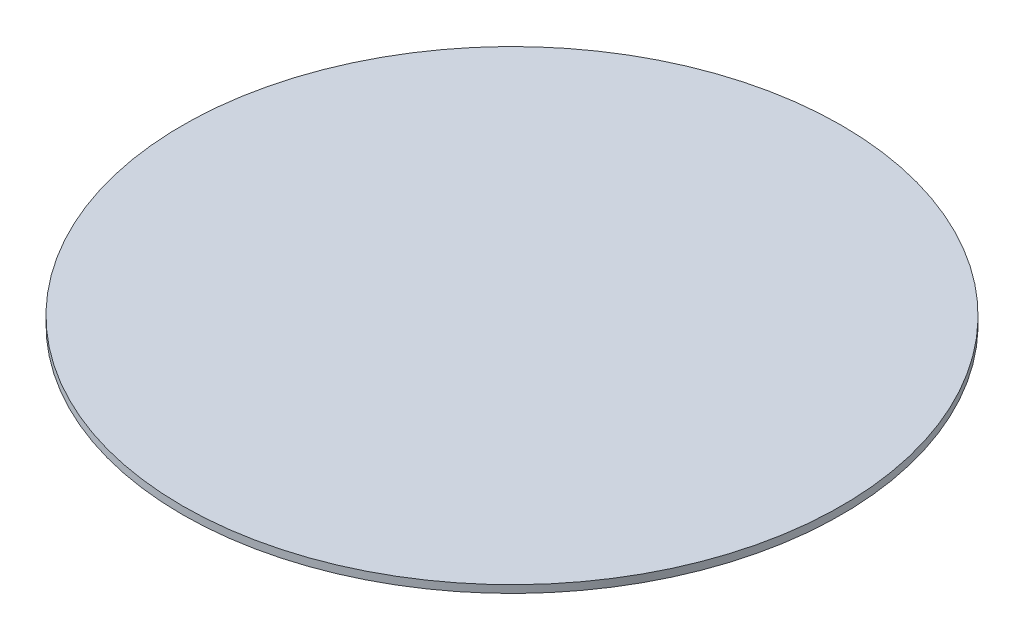
SolidWorks part; units mm, degrees
material "Стекло"
ref_plane "Front" through (0, 0, 0) normal (0, 0, 1) x (1, 0, 0)
ref_plane "Top" through (0, 0, 0) normal (0, 1, 0) x (1, 0, 0)
ref_plane "Right" through (0, 0, 0) normal (1, 0, 0) x (0, 0, -1)
sketch "Эскиз1" plane through (0, 0, 0) normal (0, 1, 0) x (1, 0, 0)
  circle A0 centre (0, 0) radius 130
  dimension "D1" = 260
extrude "База" add sketch "Эскиз1" along normal blind 3
